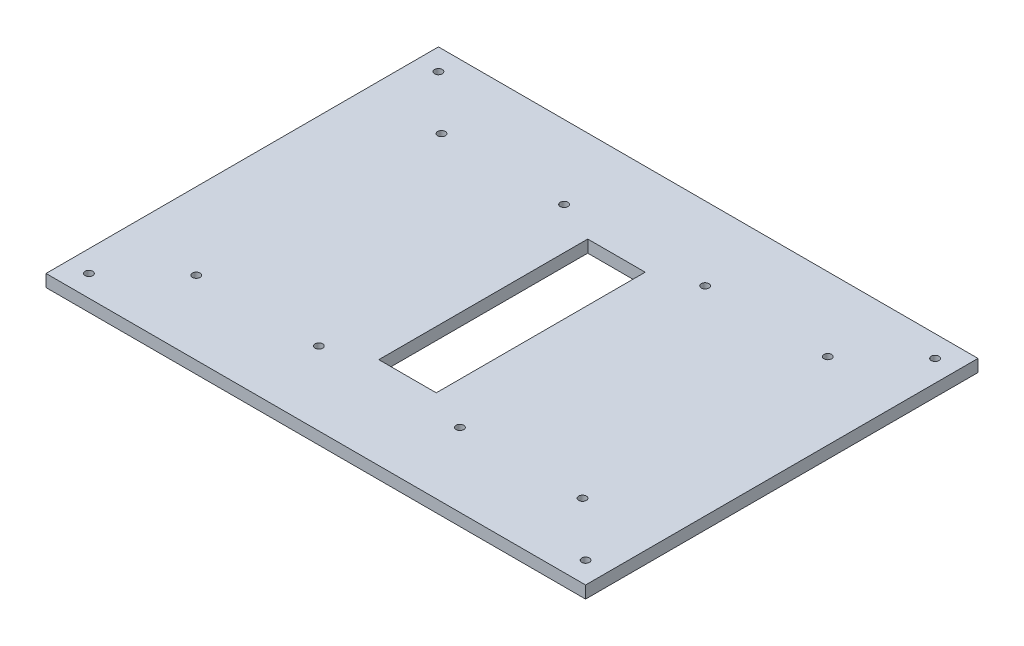
SolidWorks part; units mm, degrees
ref_plane "前视基准面" through (0, 0, 0) normal (0, 0, 1) x (1, 0, 0)
ref_plane "上视基准面" through (0, 0, 0) normal (0, 1, 0) x (1, 0, 0)
ref_plane "右视基准面" through (0, 0, 0) normal (1, 0, 0) x (0, 0, -1)
sketch "草图1" plane through (0, 0, 0) normal (0, 1, 0) x (1, 0, 0)
  line L1 (0, 0) -> (176, 0)
  line L2 (0, 0) -> (0, 128)
  line L3 (0, 128) -> (176, 128)
  line L4 (176, 0) -> (176, 128)
  dimension "D1" = 128
  dimension "D2" = 176
extrude "凸台-拉伸1" add sketch "草图1" along normal blind 4
sketch "草图2" plane through (0, 4, 0) normal (0, 1, 0) x (1, 0, 0)
  line L0 (0, 64) -> (176, 64) construction
  line L1 (0, 128) -> (0, 0) construction
  line L2 (176, 0) -> (176, 128) construction
  line L3 (88, 128) -> (88, 0) construction
  line L4 (176, 128) -> (0, 128) construction
  line L5 (0, 0) -> (176, 0) construction
  point P12 (7, 121)
  point P13 (7, 7)
  point P14 (169, 7)
  point P15 (169, 121)
  point P16 (25, 24)
  point P17 (65, 24)
  point P18 (65, 104)
  point P19 (25, 104)
  point P20 (111, 104)
  point P21 (151, 104)
  point P26 (111, 24)
  point P27 (151, 24)
  dimension "D1" = 7
  dimension "D2" = 7
  dimension "D3" = 25
  dimension "D4" = 40
  dimension "D5" = 40
  dimension "D6" = 40
sketch "草图3" plane through (0, 4, 0) normal (0, 1, 0) x (1, 0, 0)
  line L1 (78.6317, 98.0769) -> (97.3683, 98.0769)
  line L2 (78.6317, 98.0769) -> (78.6317, 29.9231)
  line L3 (78.6317, 29.9231) -> (97.3683, 29.9231)
  line L4 (97.3683, 98.0769) -> (97.3683, 29.9231)
  line L6 (88, 128) -> (88, 0) construction
  line L7 (0, 64) -> (176, 64) construction
  line L8 (0, 128) -> (0, 0) construction
  line L9 (176, 0) -> (176, 128) construction
extrude "切除-拉伸2" cut sketch "草图3" against normal blind 4
hole_wizard "M3 螺纹孔1" positions "草图4" profile "草图5" tap size "M3" standard "GB" end condition up to next
sketch "草图4" plane through (0, 4, 0) normal (0, 1, 0) x (1, 0, 0)
  point P0 (7, 121)
  point P3 (25, 104)
  point P6 (65, 104)
  point P9 (65, 24)
  point P12 (25, 24)
  point P15 (7, 7)
  point P18 (169, 7)
  point P21 (111, 24)
  point P24 (151, 24)
  point P27 (151, 104)
  point P30 (111, 104)
  point P33 (169, 121)
sketch "草图5" plane through (7, 4, -121) normal (1, 0, 0) x (0, 0, 1)
  line L0 (0, 0) -> (0, 4)
  line L1 (0, 4) -> (1.25, 4)
  line L2 (1.25, 4) -> (1.25, 0)
  line L5 (1.25, 0) -> (0, 0)
  line L11 (0, -6.35) -> (0, 107.95) construction
  dimension "通孔螺纹孔钻头直径" = 2.5
  dimension "通孔螺纹孔钻头深度" = 4
cosmetic thread "孔螺蚊线1"
cosmetic thread "孔螺蚊线2"
cosmetic thread "孔螺蚊线3"
cosmetic thread "孔螺蚊线4"
cosmetic thread "孔螺蚊线5"
cosmetic thread "孔螺蚊线6"
cosmetic thread "孔螺蚊线7"
cosmetic thread "孔螺蚊线8"
cosmetic thread "孔螺蚊线9"
cosmetic thread "孔螺蚊线10"
cosmetic thread "孔螺蚊线11"
cosmetic thread "孔螺蚊线12"
